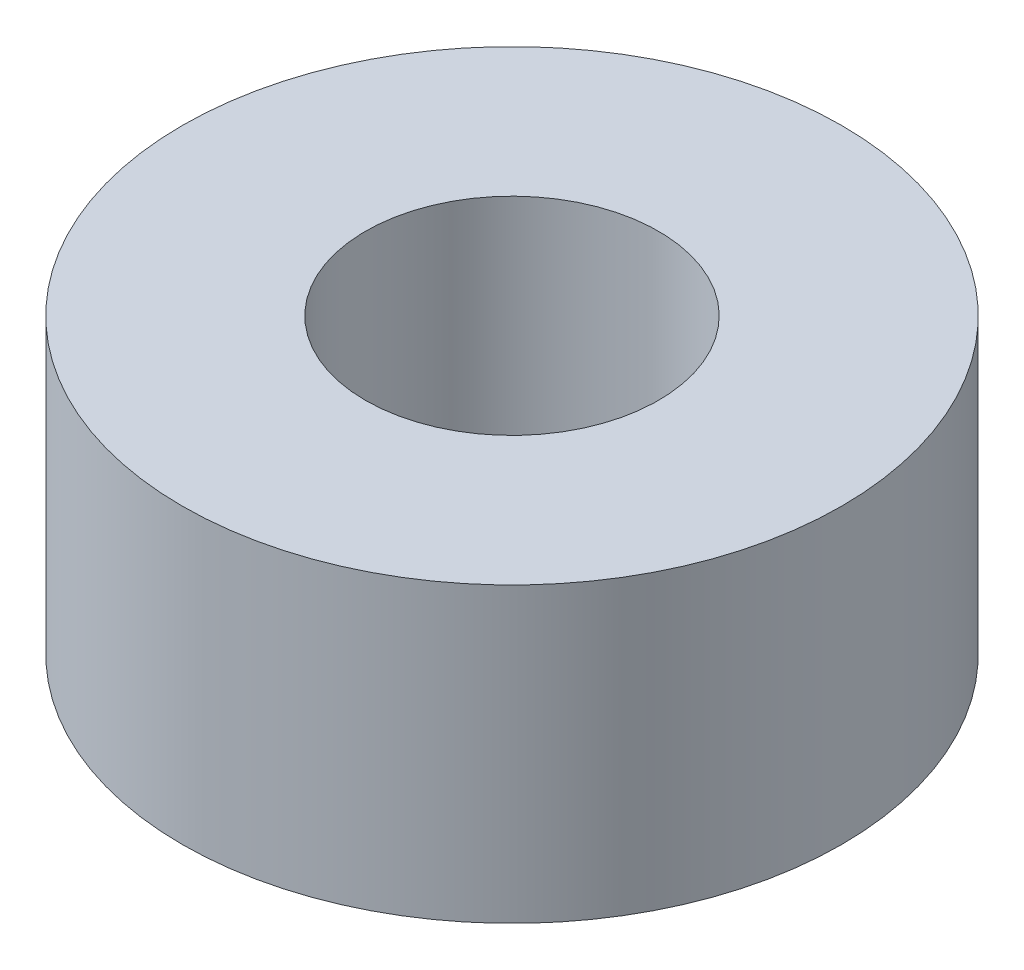
SolidWorks part; units mm, degrees
ref_plane "Front Plane" through (0, 0, 0) normal (0, 0, 1) x (1, 0, 0)
ref_plane "Top Plane" through (0, 0, 0) normal (0, 1, 0) x (1, 0, 0)
ref_plane "Right Plane" through (0, 0, 0) normal (1, 0, 0) x (0, 0, -1)
sketch "Sketch1" plane through (0, 0, 0) normal (0, 1, 0) x (1, 0, 0)
  circle A0 centre (0, 0) radius 2
  circle A1 centre (0, 0) radius 4.5
  dimension "D1" = 4
  dimension "D2" = 9
extrude "Boss-Extrude1" add sketch "Sketch1" along normal blind 4
